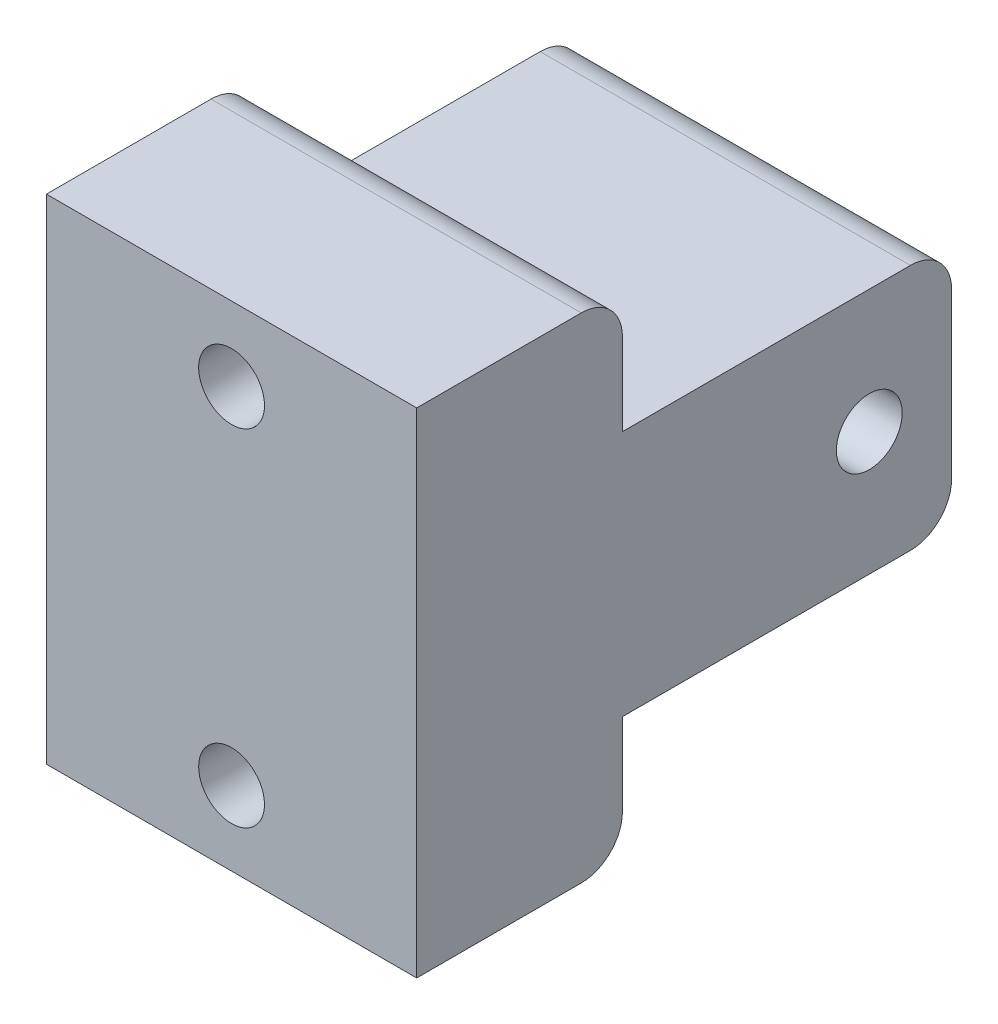
SolidWorks part; units mm, degrees
material "ABS"
ref_plane "前视基准面" through (0, 0, 0) normal (0, 0, 1) x (1, 0, 0)
ref_plane "上视基准面" through (0, 0, 0) normal (0, 1, 0) x (1, 0, 0)
ref_plane "右视基准面" through (0, 0, 0) normal (1, 0, 0) x (0, 0, -1)
other "Configuration Table"
sketch "草图1" plane through (0, 0, 0) normal (1, 0, 0) x (0, 0, -1)
  line L0 (-24.2368, 0) -> (28.3769, 0) construction
  line L1 (-20, 15) -> (15, 15)
  line L3 (-20, -15) -> (15, -15)
  line L4 (20, 10) -> (20, -10)
  line L5 (-20, 15) -> (20, -15) construction
  line L6 (-20, -15) -> (20, 15) construction
  line L7 (-20, 15) -> (-20, 25)
  line L8 (-25, -30) -> (-45, -30)
  line L9 (-20, -25) -> (-20, -15)
  line L10 (-25, 30) -> (-45, 30)
  line L11 (-45, -30) -> (-45, 30)
  line L12 (-20, -30) -> (-45, 30) construction
  line L13 (-20, 30) -> (-45, -30) construction
  line L14 (-32.5, 37.4677) -> (-32.5, -44.8857) construction
  circle A2 centre (10, 0) radius 4
  arc A3 (15, 15) -> (20, 10) centre (15, 10) cw
  arc A4 (15, -15) -> (20, -10) centre (15, -10) ccw
  arc A5 (-25, -30) -> (-20, -25) centre (-25, -25) ccw
  arc A6 (-20, 25) -> (-25, 30) centre (-25, 25) ccw
  point P0 (0, 0)
  point P8 (-32.5, 0)
  dimension "D6" = 8
  dimension "D7" = 5
  dimension "D1" = 40
  dimension "D2" = 60
  dimension "D3" = 30
  dimension "D4" = 25
  dimension "D5" = 10
extrude "凸台-拉伸1" add sketch "草图1" along normal blind 45
sketch "草图2" plane through (0, 0, 45) normal (0, 0, 1) x (1, 0, 0)
  line L0 (22.5, 30) -> (22.5, -30) construction
  line L1 (45, 30) -> (0, 30) construction
  line L2 (45, -30) -> (0, -30) construction
  line L3 (0, 0) -> (45, 0) construction
  line L4 (45, 30) -> (45, -30) construction
  circle A0 centre (22.5, 21) radius 4
  circle A1 centre (22.5, -21) radius 4
  dimension "D2" = 8
  dimension "D1" = 42
extrude "切除-拉伸1" cut sketch "草图2" against normal blind 45
